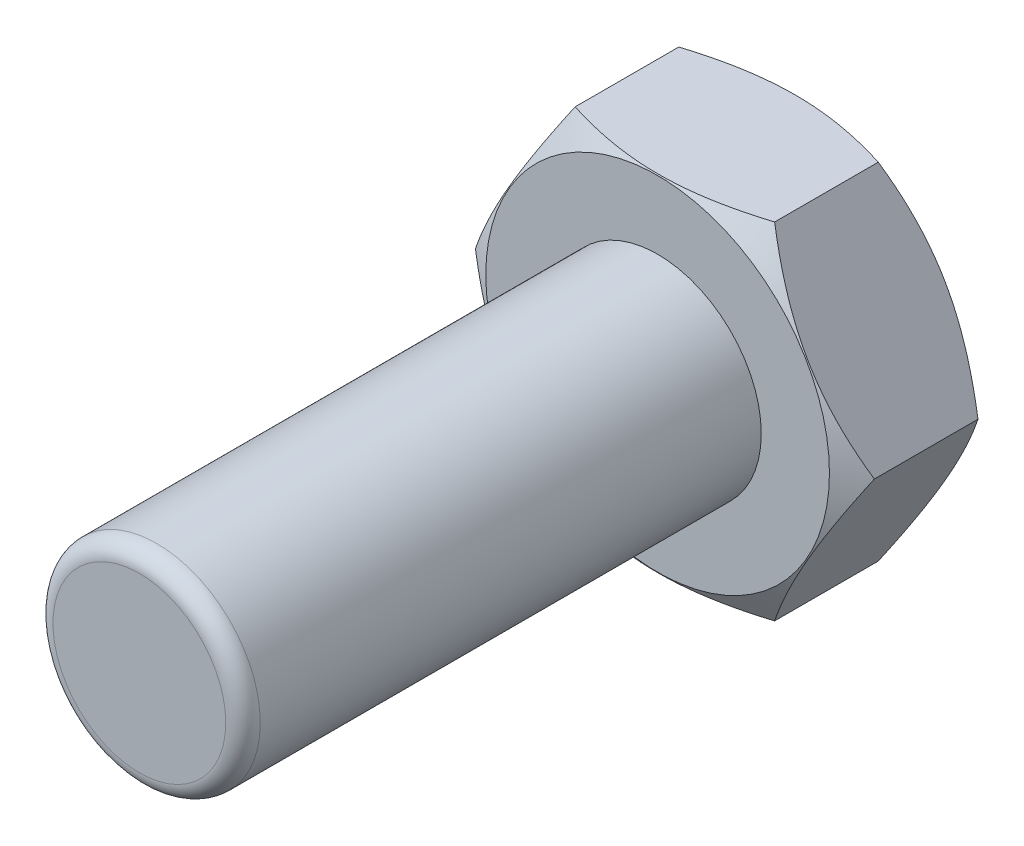
SolidWorks part; units mm, degrees
material "1.4003 (X2CrNi12)"
ref_plane "Ön Düzlem" through (0, 0, 0) normal (0, 0, 1) x (1, 0, 0)
ref_plane "Üst Düzlem" through (0, 0, 0) normal (0, 1, 0) x (1, 0, 0)
ref_plane "Sağ Düzlem" through (0, 0, 0) normal (1, 0, 0) x (0, 0, -1)
sketch "Çizim1" plane through (0, 0, 0) normal (0, 0, 1) x (1, 0, 0)
  line L1 (5.7735, 0) -> (2.8868, 5)
  line L2 (2.8868, 5) -> (-2.8868, 5)
  line L3 (-2.8868, 5) -> (-5.7735, 0)
  line L4 (-5.7735, 0) -> (-2.8868, -5)
  line L5 (-2.8868, -5) -> (2.8868, -5)
  line L6 (2.8868, -5) -> (5.7735, 0)
  circle A0 centre (0, 0) radius 5 construction
  dimension "D1" = 10
extrude "Yükseklik-Ekstrüzyon1" add sketch "Çizim1" along normal blind 4
sketch "Çizim2" plane through (0, 0, 4) normal (0, 0, 1) x (1, 0, 0)
  circle A0 centre (0, 0) radius 3
  dimension "D1" = 6
extrude "Yükseklik-Ekstrüzyon2" add sketch "Çizim2" along normal blind 15
cosmetic thread "Kozmetik Diş Açma1" parameters "D2"=4.891
sketch "Çizim3" plane through (0, 0, 0) normal (0, 1, 0) x (1, 0, 0)
  line L0 (-5.7735, 0) -> (-4.9735, 0)
  line L1 (-4.9735, 0) -> (-5.7735, -0.5)
  line L2 (-5.7735, -4) -> (-5.7735, 0) construction
  line L3 (-5.7735, -0.5) -> (-5.7735, 0)
  line L4 (-5.7735, -4) -> (-5.7735, -3.5)
  line L5 (-5.7735, -3.5) -> (-4.9735, -4)
  line L6 (-2.8868, -4) -> (-5.7735, -4) construction
  line L7 (-4.9735, -4) -> (-5.7735, -4)
  line L8 (0, 0) -> (0, -4) construction
  line L9 (-3, -4) -> (3, -4) construction
  dimension "D1" = 0.8
  dimension "D2" = 0.5
  dimension "D3" = 0.8
  dimension "D4" = 0.5
revolve "Kes-Döndür1" cut sketch "Çizim3" angle 360 about L8
fillet "Radyus1" radius 0.5 1 edges at (3, 0, 19)
